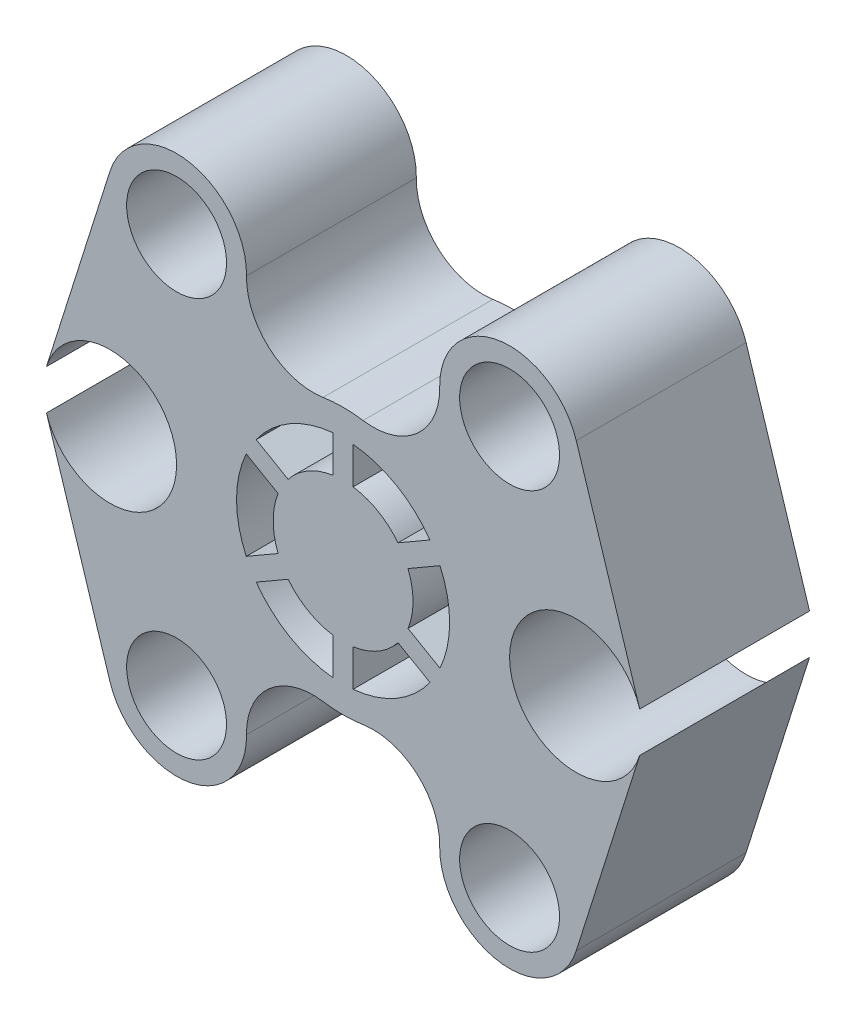
SolidWorks part; units mm, degrees
ref_plane "Front Plane" through (0, 0, 0) normal (0, 0, 1) x (1, 0, 0)
ref_plane "Top Plane" through (0, 0, 0) normal (0, 1, 0) x (1, 0, 0)
ref_plane "Right Plane" through (0, 0, 0) normal (1, 0, 0) x (0, 0, -1)
sketch "Sketch1" plane through (0, 0, 0) normal (0, 0, 1) x (1, 0, 0)
  line L0 (0, -1000) -> (0, 49000) construction
  line L1 (-1000, 0) -> (49000, 0) construction
  line L2 (-70.0249, 66.325) -> (-89.0713, 6.0238)
  line L3 (-70.0249, -66.325) -> (-89.0713, -6.0238)
  line L4 (70.0249, -66.325) -> (89.0713, -6.0238)
  line L5 (70.0249, 66.325) -> (89.0713, 6.0238)
  line L6 (-3, -20.7846) -> (-3, -31.8591)
  line L7 (3, -20.7846) -> (3, -31.8591)
  line L8 (-19.5, -7.7942) -> (-29.0908, -13.3315)
  line L9 (-16.5, -12.9904) -> (-26.0908, -18.5276)
  line L10 (-16.5, 12.9904) -> (-26.0908, 18.5276)
  line L11 (-19.5, 7.7942) -> (-29.0908, 13.3315)
  line L12 (3, 20.7846) -> (3, 31.8591)
  line L13 (-3, 20.7846) -> (-3, 31.8591)
  line L14 (19.5, 7.7942) -> (29.0908, 13.3315)
  line L15 (16.5, 12.9904) -> (26.0908, 18.5276)
  line L16 (16.5, -12.9904) -> (26.0908, -18.5276)
  line L17 (19.5, -7.7942) -> (29.0908, -13.3315)
  circle A0 centre (0, 0) radius 40
  circle A1 centre (-50, 60) radius 15
  arc A2 (-70.0249, 66.325) -> (-29.0029, 59.6519) centre (-50, 60) cw
  arc A3 (-29.0029, 59.6519) -> (-6.0038, 39.5469) centre (-9.0056, 59.3203) ccw
  circle A4 centre (-70, 0) radius 20
  arc A5 (-29.0029, -59.6519) -> (-6.0038, -39.5469) centre (-9.0056, -59.3203) cw
  arc A6 (-70.0249, -66.325) -> (-29.0029, -59.6519) centre (-50, -60) ccw
  circle A7 centre (-50, -60) radius 15
  arc A8 (29.0029, -59.6519) -> (6.0038, -39.5469) centre (9.0056, -59.3203) ccw
  arc A9 (70.0249, -66.325) -> (29.0029, -59.6519) centre (50, -60) cw
  circle A10 centre (50, -60) radius 15
  circle A11 centre (70, 0) radius 20
  arc A12 (29.0029, 59.6519) -> (6.0038, 39.5469) centre (9.0056, 59.3203) cw
  arc A13 (70.0249, 66.325) -> (29.0029, 59.6519) centre (50, 60) ccw
  circle A14 centre (50, 60) radius 15
  circle A15 centre (-70, 0) radius 15
  circle A16 centre (70, 0) radius 15
  arc A17 (3, -31.8591) -> (26.0908, -18.5276) centre (0, 0) ccw
  arc A18 (3, -20.7846) -> (16.5, -12.9904) centre (0, 0) ccw
  arc A19 (29.0908, -13.3315) -> (29.0908, 13.3315) centre (0, 0) ccw
  arc A20 (19.5, -7.7942) -> (19.5, 7.7942) centre (0, 0) ccw
  arc A21 (16.5, 12.9904) -> (3, 20.7846) centre (0, 0) ccw
  arc A22 (26.0908, 18.5276) -> (3, 31.8591) centre (0, 0) ccw
  arc A23 (-3, 31.8591) -> (-26.0908, 18.5276) centre (0, 0) ccw
  arc A24 (-3, 20.7846) -> (-16.5, 12.9904) centre (0, 0) ccw
  arc A25 (-29.0908, 13.3315) -> (-29.0908, -13.3315) centre (0, 0) ccw
  arc A26 (-19.5, 7.7942) -> (-19.5, -7.7942) centre (0, 0) ccw
  arc A27 (-26.0908, -18.5276) -> (-3, -31.8591) centre (0, 0) ccw
  arc A28 (-16.5, -12.9904) -> (-3, -20.7846) centre (0, 0) ccw
  point P67 (0, 0)
  dimension "D1" = 80
  dimension "D2" = 30
  dimension "D5" = 21
  dimension "D6" = 20
  dimension "D7" = 40
  dimension "D9" = 30
  dimension "D10" = 64
  dimension "D11" = 42
  dimension "D3" = 50
  dimension "D4" = 60
  dimension "D8" = 20
  dimension "D12" = 3
  dimension "D14" = 6
  dimension "D13" = 6
extrude "Boss-Extrude4" add sketch "Sketch1" along normal blind 51 contours L3 A6 A5 A0 A3 A2 L2 A4 A1 A7 | L5 A13 A12 A0 A8 A9 L4 A11 A10 A14 | A0 A22 L15 A21 L12 L7 A18 L16 A17 L17 A20 L14 A19 L13 A24 L10 A23 L11 A26 L8 A25 L9 A28 L6 A27
